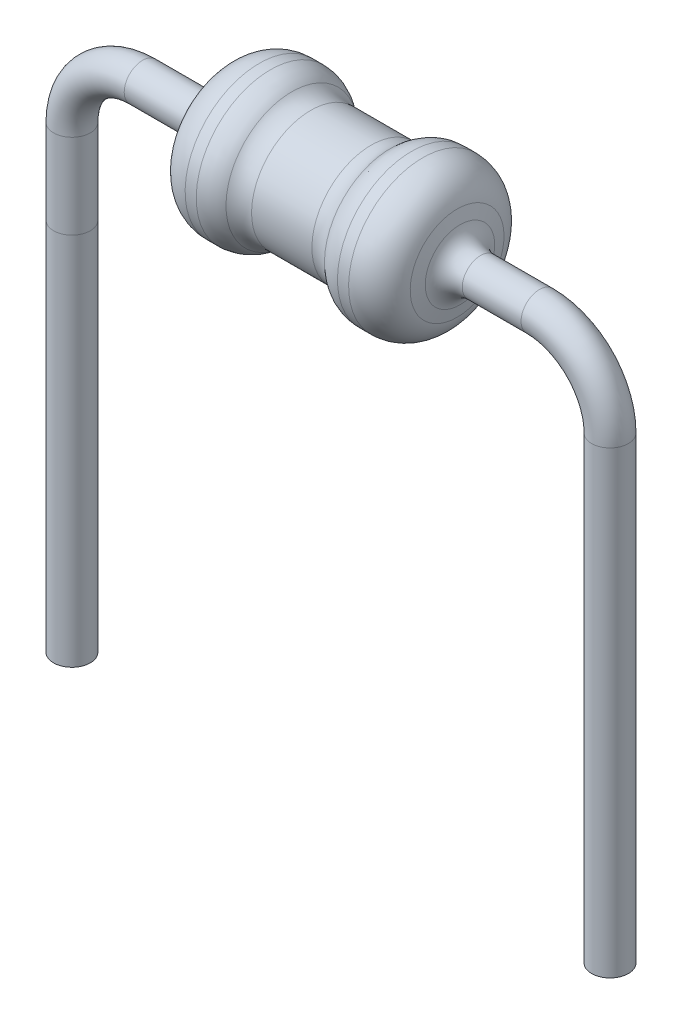
SolidWorks part; units mm, degrees
ref_plane "Front Plane" through (0, 0, 0) normal (0, 0, 1) x (1, 0, 0)
ref_plane "Top Plane" through (0, 0, 0) normal (0, 1, 0) x (1, 0, 0)
ref_plane "Right Plane" through (0, 0, 0) normal (1, 0, 0) x (0, 0, -1)
sketch "Sketch1" plane through (0, 0, 0) normal (0, 1, 0) x (1, 0, 0)
  line L0 (3.81, 0) -> (-3.81, 0) construction
  line L1 (0, 0) -> (0, 12.1522) construction
  circle A0 centre (-3.81, 0) radius 0.26
  circle A1 centre (3.81, 0) radius 0.26
  dimension "D2" = 0.52
  dimension "D1" = 3.81
extrude "Boss-Extrude1" add sketch "Sketch1" along normal blind 5.3
sketch "Sketch2" plane through (0, 0, 0) normal (0, 0, 1) x (1, 0, 0)
  line L0 (-1.8, 7.5) -> (1.8, 7.5)
  line L1 (0, 0) -> (0, 7.5) construction
  line L2 (1, 8.55) -> (1.1574, 8.55)
  line L3 (1.8, 7.5) -> (1.6442, 8.1642)
  line L4 (-1.8, 7.5) -> (-1.6442, 8.1642)
  line L5 (-0.4272, 8.3392) -> (0.4272, 8.3392)
  line L7 (-1, 7.5001) -> (-1, 9.3288) construction
  line L13 (-1, 8.55) -> (-1.1574, 8.55)
  arc A0 (-1.6442, 8.1642) -> (-1.1574, 8.55) centre (-1.1574, 8.05) cw
  arc A1 (-1, 8.55) -> (-0.6972, 8.4314) centre (-1, 8.1043) cw
  arc A2 (-0.6972, 8.4314) -> (-0.4272, 8.3392) centre (-0.4584, 8.6893) ccw
  arc A3 (0.6972, 8.4314) -> (0.4272, 8.3392) centre (0.4584, 8.6893) cw
  arc A4 (1, 8.55) -> (0.6972, 8.4314) centre (1, 8.1043) ccw
  arc A5 (1.6442, 8.1642) -> (1.1574, 8.55) centre (1.1574, 8.05) ccw
  point P10 (0, 10.5)
  point P11 (-4.572, 10.5)
  point P14 (0.428, 7.5)
  point P17 (0.428, 11)
  dimension "D1" = 0.5
  dimension "D2" = 3.6
revolve "Revolve1" add sketch "Sketch2" angle 360 about L0
sketch "Sketch3" plane through (0, 0, 0) normal (0, 0, 1) x (1, 0, 0)
  line L0 (1.568, 7.5) -> (-3.5, 7.5) construction
  line L1 (3.55, 0) -> (4.07, 0) construction
  line L3 (0, 7.5) -> (0, 4.5) construction
  line L5 (1.568, 7.5) -> (2.81, 7.5)
  line L6 (3.81, 6.5) -> (3.81, 5.3)
  line L7 (4.07, 5.3) -> (3.55, 5.3) construction
  arc A0 (3.81, 6.5) -> (2.81, 7.5) centre (2.81, 6.5) ccw
  dimension "D1" = 1.2
  dimension "D3" = 1
  dimension "D2" = 7.5
sketch "Sketch4" plane through (0, 5.3, 0) normal (0, 1, 0) x (1, 0, 0)
  circle A2 centre (3.81, 0) radius 0.26
  dimension "D1" = 0.52
sweep "Sweep1" add profiles "Sketch4" path "Sketch3"
mirror "Mirror1" about plane through (0, 0, 0) normal (1, 0, 0) of "Sweep1"
fillet "Fillet2" radius 0.3 2 edges at (-1.739, 7.76, 0) (1.739, 7.24, 0)
